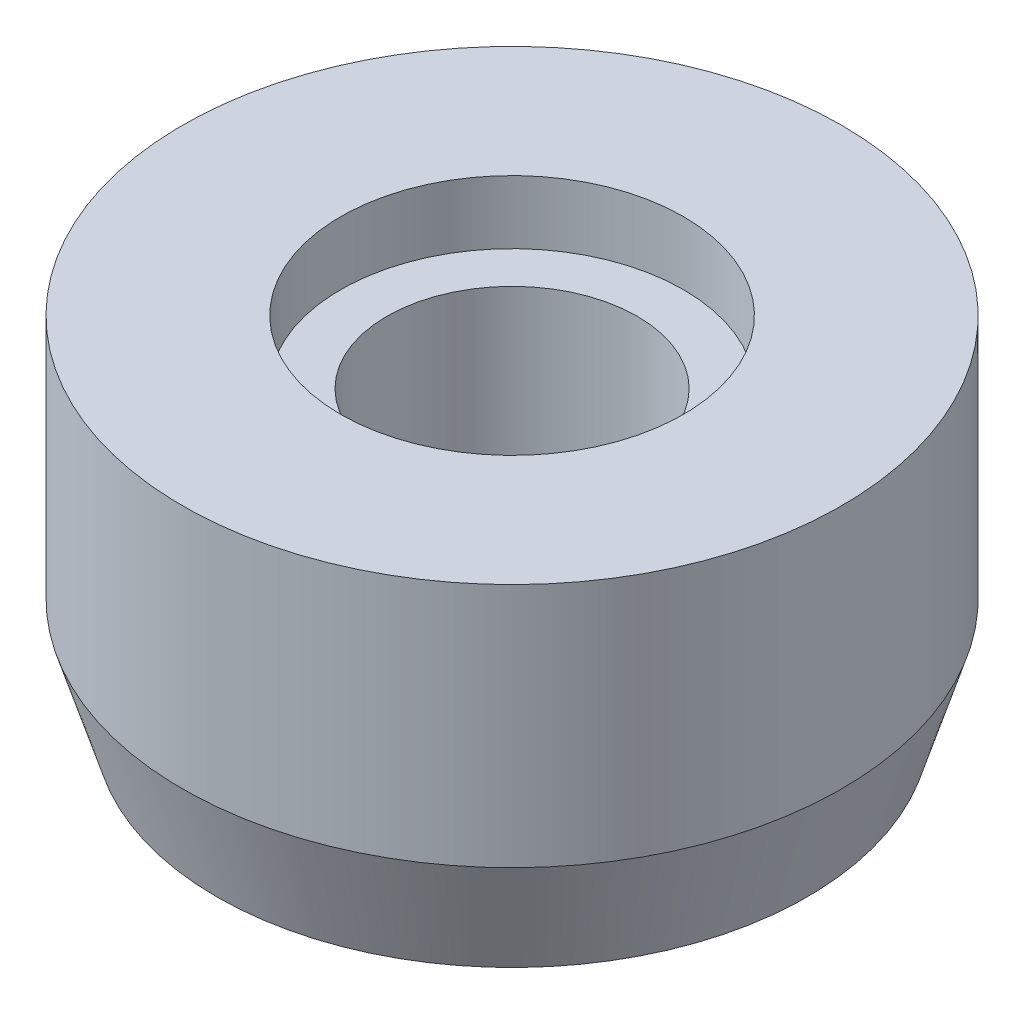
SolidWorks part; units mm, degrees
ref_plane "Front Plane" through (0, 0, 0) normal (0, 0, 1) x (1, 0, 0)
ref_plane "Top Plane" through (0, 0, 0) normal (0, 1, 0) x (1, 0, 0)
ref_plane "Right Plane" through (0, 0, 0) normal (1, 0, 0) x (0, 0, -1)
sketch "Sketch1" plane through (0, 0, 0) normal (0, 0, 1) x (1, 0, 0)
  line L0 (0, 0) -> (0, 36.656) construction
  line L1 (4.75, 15.4979) -> (4.75, 26.5857)
  line L2 (4.75, 26.5857) -> (6.5, 26.5857)
  line L3 (6.5, 26.5857) -> (6.5, 28.9857)
  line L4 (6.5, 28.9857) -> (12.5, 28.9857)
  line L5 (12.5, 28.9857) -> (12.5, 19.6857)
  line L6 (12.5, 19.6857) -> (11.2, 15.4877)
  line L7 (11.2, 15.4877) -> (4.75, 15.4979)
  point P5 (0, 0)
  point P11 (0, 0)
  dimension "D1" = 4.75
  dimension "D2" = 2.4
  dimension "D3" = 6
  dimension "D4" = 12.5
  dimension "D5" = 13.5
  dimension "D6" = 4.2
  dimension "D7" = 6.45
revolve "Revolve1" add sketch "Sketch1" angle 360 about L0
